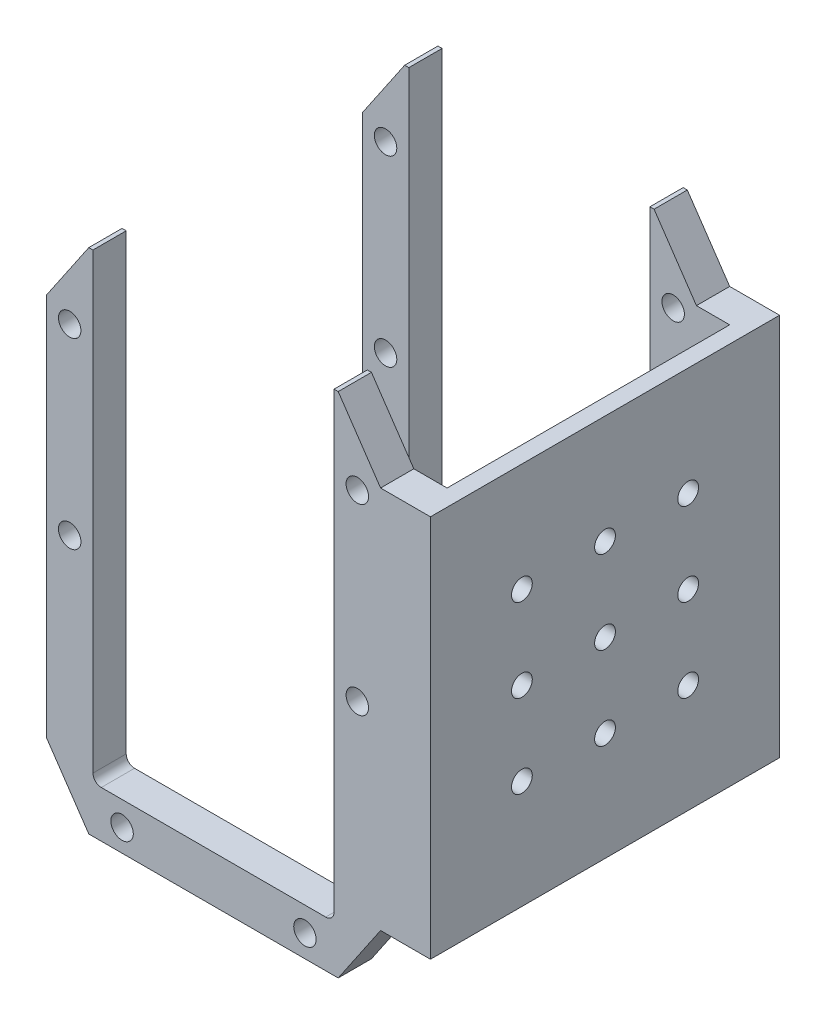
SolidWorks part; units mm, degrees
ref_plane "정면" through (0, 0, 0) normal (0, 0, 1) x (1, 0, 0)
ref_plane "윗면" through (0, 0, 0) normal (0, 1, 0) x (1, 0, 0)
ref_plane "우측면" through (0, 0, 0) normal (1, 0, 0) x (0, 0, -1)
sketch "스케치1" plane through (0, 0, 0) normal (0, 0, 1) x (1, 0, 0)
  line L0 (-14.5, -41.5) -> (-14.5, 11.5)
  line L1 (-14.5, 13) -> (-15, 13)
  line L2 (-15, 13) -> (-20.1, 5.5)
  line L3 (-20.1, 5.5) -> (-20.1, -40.6)
  line L4 (-20.1, -40.6) -> (-15, -48.1)
  line L5 (-15, -48.1) -> (15, -48.1)
  line L6 (15, -48.1) -> (20.1, -40.6)
  line L7 (20.1, -40.6) -> (20.1, 5.5)
  line L8 (20.1, 5.5) -> (15, 13)
  line L9 (15, 13) -> (14.5, 13)
  line L10 (14.5, 11.5) -> (14.5, -41.5)
  line L11 (13.5, -42.5) -> (-13.5, -42.5)
  line L12 (0, 0) -> (0, 13) construction
  line L13 (0, 13) -> (0, -42.5) construction
  line L14 (-14.5, 11.5) -> (-14.5, 13)
  line L15 (14.5, 11.5) -> (14.5, 13)
  arc A0 (-13.5, -42.5) -> (-14.5, -41.5) centre (-13.5, -41.5) cw
  arc A3 (14.5, -41.5) -> (13.5, -42.5) centre (13.5, -41.5) cw
  circle A4 centre (-17.3, -18.13) radius 1.35
  circle A5 centre (-17.3, 3.87) radius 1.35
  circle A6 centre (-11, -45.4056) radius 1.35
  circle A7 centre (11, -45.4056) radius 1.35
  circle A8 centre (17.3, -18.13) radius 1.35
  circle A9 centre (17.3, 3.87) radius 1.35
  dimension "D1" = 2.7
  dimension "D3" = 22
  dimension "D4" = 6.3
  dimension "D8" = 15
  dimension "D9" = 1
  dimension "D2" = 17.3
  dimension "D5" = 14.5
  dimension "D6" = 20.1
  dimension "D7" = 7.5
  dimension "D10" = 3.87
  dimension "D11" = 5.5
  dimension "D12" = 11.5
  dimension "D13" = 40.6
  dimension "D15" = 42.5
  dimension "D16" = 45.4056
extrude "보스-돌출2" add sketch "스케치1" along normal blind 42 contours L3 L4 L5 L6 L7 L8 L9 L15 L10 A3 L11 A0 L0 L14 L1 L2
sketch "스케치2" plane through (0, 0, 0) normal (0, 0, -1) x (-1, 0, 0)
  circle A1 centre (-11, -45.4056) radius 1.35
  circle A2 centre (-11, -45.4056) radius 1.35
  circle A3 centre (11, -45.4056) radius 1.35
  circle A4 centre (11, -45.4056) radius 1.35
  circle A5 centre (17.3, 3.87) radius 1.35
  circle A6 centre (17.3, 3.87) radius 1.35
  circle A7 centre (17.3, -18.13) radius 1.35
  circle A8 centre (17.3, -18.13) radius 1.35
  circle A9 centre (-17.3, 3.87) radius 1.35
  circle A10 centre (-17.3, 3.87) radius 1.35
  circle A11 centre (-17.3, -18.13) radius 1.35
  circle A12 centre (-17.3, -18.13) radius 1.35
  dimension "D1" = 0
  dimension "D2" = 0
  dimension "D3" = 0
  dimension "D4" = 0
  dimension "D5" = 0
  dimension "D6" = 0
extrude "컷-돌출1" cut sketch "스케치2" against normal blind 45
sketch "스케치3" plane through (20.1, 0, 0) normal (1, 0, 0) x (0, 0, -1)
  line L0 (-38, 5.5) -> (-38, -40.6)
  line L1 (-42, 5.5) -> (0, 5.5) construction
  line L2 (-42, -40.6) -> (0, -40.6) construction
  line L3 (-38, 5.5) -> (-38, 13)
  line L4 (-4, -40.6) -> (-4, 5.5)
  line L5 (-42, 13) -> (0, 13) construction
  line L6 (-42, -40.6) -> (-42, 5.5) construction
  line L7 (0, -40.6) -> (0, 5.5) construction
  line L8 (-38, 13) -> (-4, 13)
  line L9 (-4, 13) -> (-4, 5.5)
  line L10 (-4, -40.6) -> (-4, -48.1)
  line L11 (-42, -48.1) -> (0, -48.1) construction
  line L12 (-4, -48.1) -> (-38, -48.1)
  line L13 (-38, -48.1) -> (-38, -40.6)
  dimension "D1" = 4
  dimension "D2" = 4
  dimension "D3" = 34
extrude "컷-돌출2" cut sketch "스케치3" against normal blind 45
sketch "스케치4" plane through (20.1, 0, 0) normal (1, 0, 0) x (0, 0, -1)
  line L0 (-42, 5.5) -> (-38, 5.5)
  line L1 (-38, 5.5) -> (-38, -40.6)
  line L2 (-38, 5.5) -> (-38, -40.6) construction
  line L3 (-38, -40.6) -> (-42, -40.6)
  line L4 (-42, -40.6) -> (-42, 5.5)
  line L5 (-4, 5.5) -> (0, 5.5)
  line L6 (0, 5.5) -> (0, -40.6)
  line L7 (0, -40.6) -> (-4, -40.6)
  line L8 (-4, -40.6) -> (-4, 5.5)
extrude "보스-돌출3" add sketch "스케치4" along normal blind 4
sketch "스케치5" plane through (0, 0, 42) normal (0, 0, 1) x (1, 0, 0)
  line L0 (24.1, 5.5) -> (26.1, 5.5)
  line L1 (26.1, 5.5) -> (26.1, -40.6)
  line L2 (26.1, -40.6) -> (24.1, -40.6)
  line L3 (24.1, -40.6) -> (24.1, 5.5)
  dimension "D1" = 2
extrude "보스-돌출4" add sketch "스케치5" against normal blind 42
sketch "스케치6" plane through (26.1, 0, 0) normal (1, 0, 0) x (0, 0, -1)
  line L0 (-21, 5.5) -> (-21, -40.6) construction
  line L1 (0, 5.5) -> (-42, 5.5) construction
  line L2 (0, -40.6) -> (-42, -40.6) construction
  line L3 (0, -17.55) -> (-42, -17.55) construction
  line L4 (0, -40.6) -> (0, 5.5) construction
  line L5 (-42, -40.6) -> (-42, 5.5) construction
  circle A9 centre (-21, -17.55) radius 1.25
  circle A10 centre (-11, -17.55) radius 1.25
  circle A11 centre (-31, -17.55) radius 1.25
  circle A12 centre (-31, -7.55) radius 1.25
  circle A13 centre (-21, -7.55) radius 1.25
  circle A14 centre (-11, -7.55) radius 1.25
  circle A15 centre (-31, -27.55) radius 1.25
  circle A16 centre (-21, -27.55) radius 1.25
  circle A17 centre (-11, -27.55) radius 1.25
  dimension "D2" = 2.5
  dimension "D7" = 11
  dimension "D8" = 31
  dimension "D14" = 13.05
  dimension "D18" = 33.05
  dimension "D3" = 2
  dimension "D4" = 2
  dimension "D5" = 2
  dimension "D6" = 2
extrude "컷-돌출3" cut sketch "스케치6" against normal blind 10
